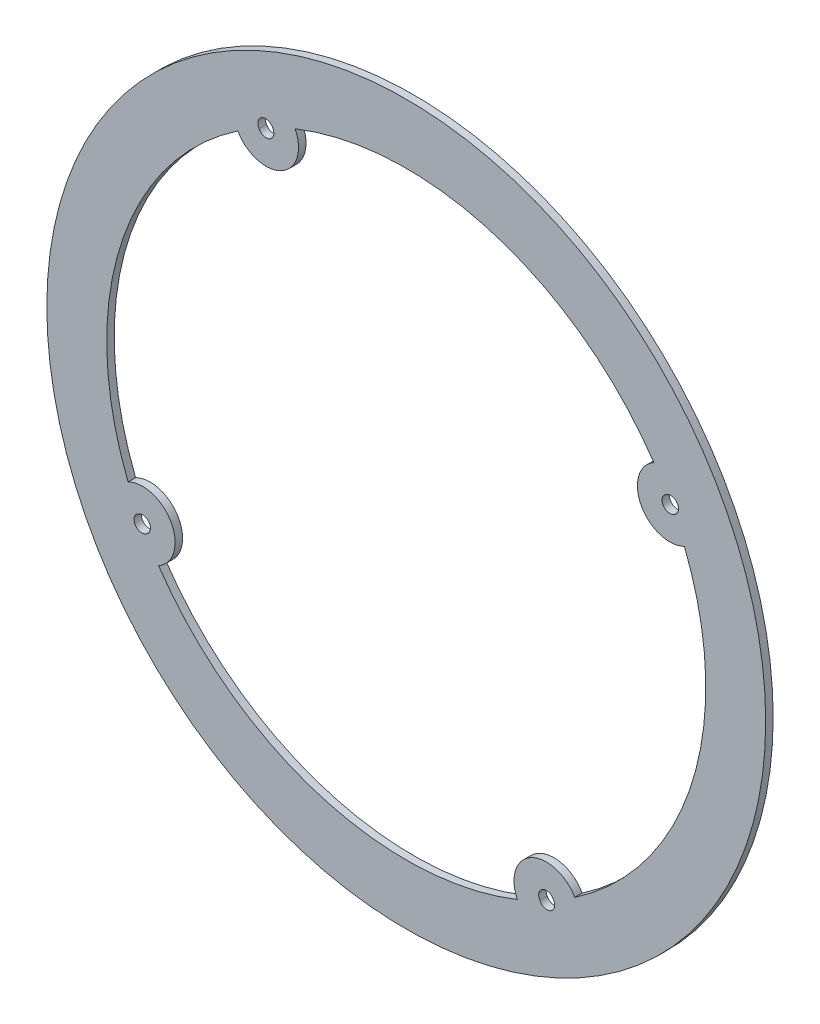
SolidWorks part; units mm, degrees
material "Magnesium Alloy"
ref_plane "Front Plane" through (0, 0, 0) normal (0, 0, 1) x (1, 0, 0)
ref_plane "Top Plane" through (0, 0, 0) normal (0, 1, 0) x (1, 0, 0)
ref_plane "Right Plane" through (0, 0, 0) normal (1, 0, 0) x (0, 0, -1)
sketch "Sketch1" plane through (0, 0, 0) normal (0, 0, 1) x (1, 0, 0)
  circle A0 centre (0, 0) radius 63.5
  circle A1 centre (0, 0) radius 76.2
  dimension "D1" = 152.4
  dimension "D2" = 127
extrude "Boss-Extrude1" add sketch "Sketch1" along normal blind 1.5875
sketch "Sketch2" plane through (0, 0, 1.5875) normal (0, 0, 1) x (1, 0, 0)
  line L0 (0, -55) -> (0, 55) construction
  line L1 (55, 0) -> (-55, 0) construction
  line L2 (-36.4961, 54.6811) -> (-25.3, 61.1583)
  circle A0 centre (-29.718, 55.88) radius 1.651
  arc A1 (-25.3, 61.1583) -> (-36.4961, 54.6811) centre (-29.718, 55.88) cw
  dimension "D1" = 3.302
  dimension "D2" = 29.718
  dimension "D3" = 55.88
extrude "Boss-Extrude2" add sketch "Sketch2" against normal blind 1.5875
sketch "Sketch4" plane through (0, 0, 1.5875) normal (0, 0, 1) x (1, 0, 0)
  circle A0 centre (-29.8162, 56.0646) radius 1.651
  arc A1 (-28.358, 56.8161) -> (-31.2545, 55.2758) centre (0, 0) ccw construction
extrude "Cut-Extrude2" cut sketch "Sketch4" against normal blind 1.5875
pattern_circular "CirPattern2" count 4 over 360 about axis through (0, 0, 0) along (0, 0, 1) of "Boss-Extrude2"
pattern_circular "CirPattern3" count 4 over 360 about axis through (0, 0, 0) along (0, 0, 1) of "Cut-Extrude2"
